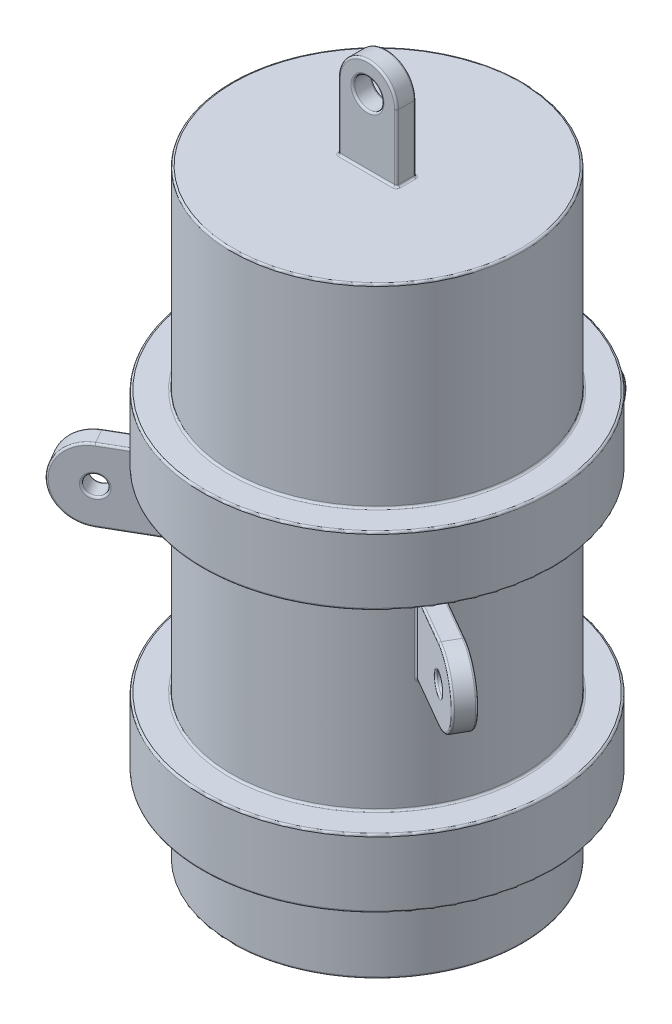
SolidWorks part; units mm, degrees
ref_plane "Front Plane" through (0, 0, 0) normal (0, 0, 1) x (1, 0, 0)
ref_plane "Top Plane" through (0, 0, 0) normal (0, 1, 0) x (1, 0, 0)
ref_plane "Right Plane" through (0, 0, 0) normal (1, 0, 0) x (0, 0, -1)
sketch "Sketch1" plane through (0, 0, 0) normal (0, 0, 1) x (1, 0, 0)
  line L0 (0, 0) -> (0, 62) construction
  line L1 (-4, 0) -> (-15, 0)
  line L2 (-15, 0) -> (-15, 8)
  line L3 (-15, 8) -> (-18, 8)
  line L4 (-18, 8) -> (-18, 15)
  line L5 (-18, 15) -> (-15, 15)
  line L6 (-15, 15) -> (-15, 35)
  line L7 (-15, 35) -> (-18, 35)
  line L8 (-18, 35) -> (-18, 42)
  line L9 (-18, 42) -> (-15, 42)
  line L10 (-15, 42) -> (-15, 62)
  line L11 (-15, 62) -> (0, 62)
  line L12 (-4, 1) -> (-14, 1)
  line L13 (-14, 1) -> (-14, 9)
  line L14 (-14, 9) -> (-17, 9)
  line L15 (-17, 9) -> (-17, 14)
  line L16 (-17, 14) -> (-14, 14)
  line L17 (-14, 14) -> (-14, 36)
  line L18 (-14, 36) -> (-17, 36)
  line L19 (-17, 36) -> (-17, 41)
  line L20 (-17, 41) -> (-14, 41)
  line L21 (-14, 41) -> (-14, 61)
  line L22 (-14, 61) -> (0, 61)
  line L23 (0, 62) -> (0, 61)
  line L24 (-4, 1) -> (-4, 0)
  dimension "D1" = 11
  dimension "D2" = 4
  dimension "D3" = 8
  dimension "D4" = 7
  dimension "D5" = 20
  dimension "D6" = 20
  dimension "D7" = 3
  dimension "D8" = 3
  dimension "D9" = 7
  dimension "D10" = 3
  dimension "D11" = 3
  dimension "D12" = 1
revolve "Revolve1" add sketch "Sketch1" angle 360 about L0
sketch "Sketch2" plane through (0, 0, 0) normal (0, 0, 1) x (1, 0, 0)
  line L0 (-3, 62) -> (3, 62)
  line L1 (15, 62) -> (-15, 62) construction
  line L2 (-3, 62) -> (-3, 68.8851)
  line L3 (-3, 68.8851) -> (3, 68.8851) construction
  line L4 (3, 68.8851) -> (3, 62)
  circle A4 centre (0, 68.8851) radius 1.5
  arc A5 (-3, 68.8851) -> (3, 68.8851) centre (0, 68.8851) cw
  point P6 (0, 62)
  dimension "D1" = 3
  dimension "D2" = 1.5
extrude "Boss-Extrude1" add sketch "Sketch2" along normal mid plane 2
sketch "Sketch3" plane through (0, 0, 0) normal (1, 0, 0) x (0, 0, -1)
  line L0 (14, 34) -> (21, 34)
  line L1 (14, 14) -> (14, 36) construction
  line L2 (21, 34) -> (21, 26.5) construction
  line L3 (21, 26.5) -> (14, 26.5)
  line L4 (14, 26.5) -> (14, 34)
  line L5 (-18, 35) -> (18, 35) construction
  circle A0 centre (21, 30.25) radius 1
  arc A1 (21, 34) -> (21, 26.5) centre (21, 30.25) cw
  dimension "D3" = 2
  dimension "D1" = 7
  dimension "D2" = 1
  dimension "D4" = 7.5
extrude "Boss-Extrude2" add sketch "Sketch3" along normal mid plane 2
pattern_circular "CirPattern1" count 3 over 360 about axis through (0, 0, 0) along (0, 1, 0) of "Boss-Extrude2"
fillet "Fillet1" radius 0.2 70 edges at (-18.5526, 30.25, 11.866) (-19.5526, 30.25, 10.134) (-15.074, 26.5, 9.8577) (-20.9341, 30.25, 13.241) (-15.074, 34, 9.8577) (-16.074, 26.5, 8.1256) (-21.9341, 30.25, 11.509) (-16.074, 34, 8.1256) (-12.9904, 34, 7.5) (-12.9904, 26.5, 7.5) (19.5526, 30.25, 10.134) (18.5526, 30.25, 11.866) (16.074, 26.5, 8.1256) (21.9341, 30.25, 11.509) (16.074, 34, 8.1256) (15.074, 26.5, 9.8577) (20.9341, 30.25, 13.241) (15.074, 34, 9.8577) (12.9904, 34, 7.5) (12.9904, 26.5, 7.5) (-1, 30.25, -22) (1, 30.25, -22) (-1, 26.5, -17.9833) (-1, 30.25, -24.75) (-1, 34, -17.9833) (1, 26.5, -17.9833) (1, 30.25, -24.75) (1, 34, -17.9833) (0, 34, -15) (0, 26.5, -15) (1.5, 68.8851, -1) (1.5, 68.8851, 1) (-3, 65.4426, -1) (0, 62, -1) (3, 65.4426, -1) (0, 71.8851, -1) (-3, 65.4426, 1) (0, 62, 1) (3, 65.4426, 1) (0, 71.8851, 1) (3, 62, 0) (-3, 62, 0) (4, 1, 0) (14, 1, 0) (14, 9, 0) (17, 9, 0) (17, 14, 0) (14, 14, 0) (14, 36, 0) (17, 36, 0) (17, 41, 0) (14, 41, 0) (14, 61, 0) (15, 42, 0) (18, 42, 0) (18, 35, 0) (15, 35, 0) (15, 15, 0) (18, 15, 0) (18, 8, 0) (15, 8, 0) (15, 0, 0) (4, 0, 0) (-1, 30.25, -14.9666) (1, 30.25, -14.9666) (13.4615, 30.25, 6.6173) (12.4615, 30.25, 8.3493) (-12.4615, 30.25, 8.3493) (-13.4615, 30.25, 6.6173) (15, 62, 0)
